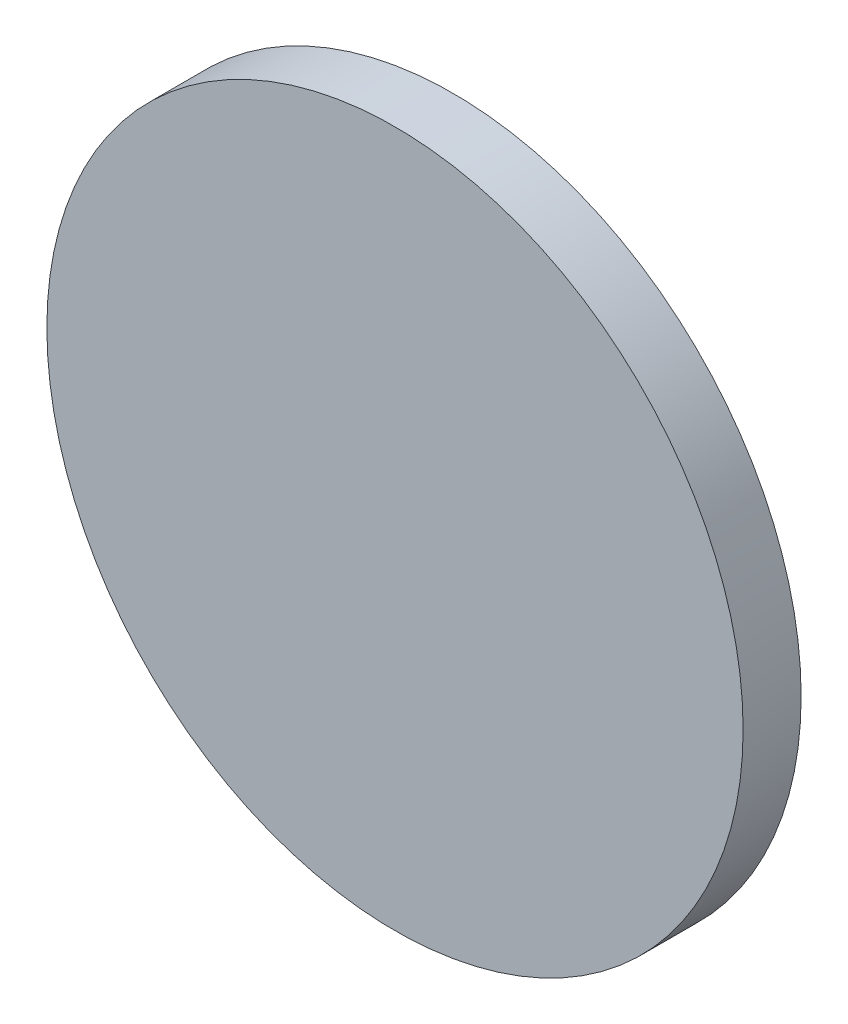
SolidWorks part; units mm, degrees
ref_plane "Front Plane" through (0, 0, 0) normal (0, 0, 1) x (1, 0, 0)
ref_plane "Top Plane" through (0, 0, 0) normal (0, 1, 0) x (1, 0, 0)
ref_plane "Right Plane" through (0, 0, 0) normal (1, 0, 0) x (0, 0, -1)
sketch "Sketch1" plane through (0, 0, 0) normal (0, 0, 1) x (1, 0, 0)
  circle A0 centre (0, 0) radius 76.2
  circle A1 centre (0.2292, -17.0105) radius 38.1
extrude "Boss-Extrude1" add sketch "Sketch1" along normal blind 12.7 contours A0 A1
